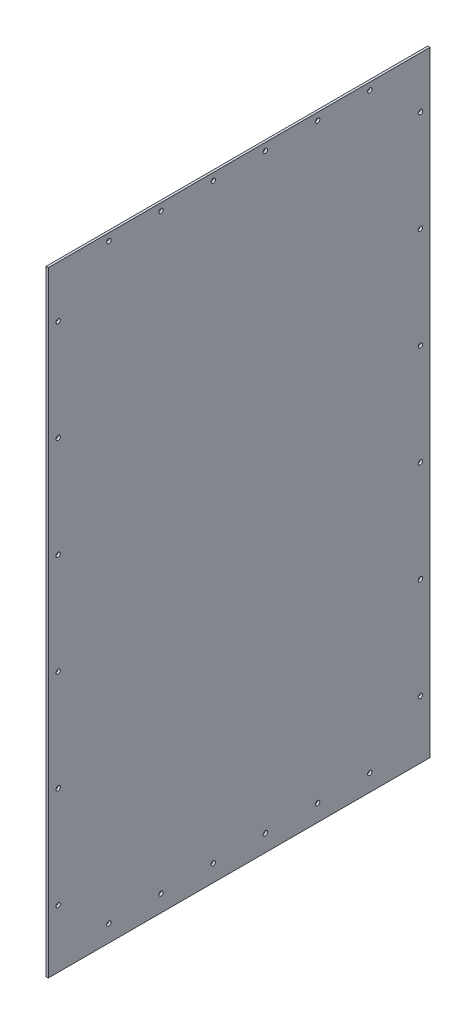
SolidWorks part; units mm, degrees
material "Acrylic (Medium-high impact)"
ref_plane "Front Plane" through (0, 0, 0) normal (0, 0, 1) x (1, 0, 0)
ref_plane "Top Plane" through (0, 0, 0) normal (0, 1, 0) x (1, 0, 0)
ref_plane "Right Plane" through (0, 0, 0) normal (1, 0, 0) x (0, 0, -1)
sketch "Sketch1" plane through (0, 0, 0) normal (1, 0, 0) x (0, 0, -1)
  line L0 (-251.1933, 404.8633) -> (-251.1933, 407.9367) construction
  line L1 (251.1933, -404.8633) -> (-251.1933, -404.8633)
  line L2 (251.1933, -404.8633) -> (251.1933, 404.8633)
  line L3 (251.1933, 404.8633) -> (-251.1933, 404.8633)
  line L4 (-251.1933, -404.8633) -> (-251.1933, 404.8633)
  line L5 (251.1933, -404.8633) -> (-251.1933, 404.8633) construction
  line L6 (251.1933, 404.8633) -> (-251.1933, -404.8633) construction
  point P0 (0, 0)
  dimension "D1" = 502.3866
  dimension "D2" = 3.0734
  dimension "D3" = 812.8
extrude "SidePanel" add sketch "Sketch1" along normal blind 3.0734
sketch "Sketch2" plane through (3.0734, 0, 0) normal (1, 0, 0) x (0, 0, -1)
  line L0 (171.9199, 404.8633) -> (171.9199, 385.8133) construction
  line L1 (251.1933, 404.8633) -> (-251.1933, 404.8633) construction
  line L3 (171.9199, -392.1633) -> (171.9199, -373.1133) construction
  line L4 (171.9199, 395.3383) -> (229.0699, 395.3383) construction
  line L5 (-251.1933, -404.8633) -> (251.1933, -404.8633) construction
  line L7 (229.0699, 395.3383) -> (248.1199, 395.3383) construction
  line L8 (248.1199, 395.3383) -> (251.1933, 395.3383) construction
  line L9 (251.1933, -404.8633) -> (251.1933, 404.8633) construction
  circle A0 centre (171.9199, 395.3383) radius 2.8956
  circle A1 centre (171.9199, -382.6383) radius 2.8956
  dimension "D3" = 5.7912
  dimension "D1" = 19.05
  dimension "D4" = 19.05
  dimension "D5" = 12.7
  dimension "D2" = 57.15
  dimension "D6" = 19.05
  dimension "D7" = 3.0734
extrude "TopBottomHoleMaster" cut sketch "Sketch2" against normal through all
pattern_linear "LPattern1" count 6 spacing 68.6906 along (0, 0, 1) of "TopBottomHoleMaster"
sketch "Sketch3" plane through (3.0734, 0, 0) normal (1, 0, 0) x (0, 0, -1)
  line L0 (251.1933, 337.4517) -> (248.1199, 337.4517) construction
  line L1 (251.1933, -404.8633) -> (251.1933, 404.8633) construction
  line L2 (248.1199, 337.4517) -> (229.0699, 337.4517) construction
  line L3 (251.1933, 404.8633) -> (251.1933, 407.9367) construction
  line L4 (251.1933, 404.8633) -> (-251.1933, 404.8633) construction
  line L5 (-250.7333, 337.4517) -> (-247.7333, 337.4517) construction
  line L6 (-250.7333, 337.4517) -> (-253.7333, 337.4517) construction
  line L8 (-247.7333, 337.4517) -> (-228.6833, 337.4517) construction
  line L11 (-253.7333, 337.4517) -> (-256.8067, 337.4517) construction
  line L12 (251.1933, -404.8633) -> (251.1933, 404.8633) construction
  circle A0 centre (-238.2083, 337.4517) radius 2.8956
  circle A1 centre (238.5949, 337.4517) radius 2.8956
  dimension "D1" = 3.0734
  dimension "D5" = 5.7912
  dimension "D2" = 19.05
  dimension "D3" = 3.0734
  dimension "D4" = 70.485
  dimension "D6" = 3
  dimension "D8" = 3.0734
  dimension "D9" = 508
extrude "RearHolesMaster" cut sketch "Sketch3" against normal through all
pattern_linear "LPattern2" count 6 spacing 133.1366 along (0, -1, 0) of "RearHolesMaster"
equation "\"Height\"= 32in"
equation "\"Width\"= 23in"
equation "\"Depth\"= 20in"
equation "\"Plexi\"= .121in"
equation "\"Cutwidth\"= .016in"
equation "\"Earsize\"= 1in + \"Cutwidth\" /2"
equation "\"Slotsize\" = 1in - \"CutWidth\" / 2"
equation "\"InnerWidth\" = \"Width\" - 2* \"Plexi\""
equation "\"InnerHeight\" = \"Height\" -2 * \"Plexi\""
equation "\"InnerDepth\" = \"Depth\" - 2*\"Plexi\""
equation "\"RearHoleSpacing\" = (\"Width\" - 2*\"RearHolesBorder\") / (\"RearNumHoles\"-1)"
equation "\"RivetDia\" = .228in"
equation "\"SlotDepth\" = \"Plexi\" + 0.75in + .005in"
equation "\"SideSlotWidth\"   = \"Plexi\"+.005in"
equation "\"SidePanelVertSpacing\" = (\"Height\"-2*(1.75-\"Plexi\")) / 5"
equation "\"BottomPanelSideHoleSpacing\" = (\"InnerDepth\"-2*(1.75-\"Plexi\")) / 4"
equation "\"D1@Sketch1\"=\"TopDepth\""
equation "\"D2@Sketch1\"=\"Plexi\""
equation "\"D1@SidePanel\"=\"Plexi\""
equation "\"MagnetThickness\"=3mm"
equation "\"MagnetDiameter\"=12mm"
equation "\"DoorPlexi\" = \"Plexi\""
equation "\"Boxsize\" = .75in"
equation "\"Boxinner\" = .625in"
equation "\"CornerCube\" = 0.75in"
equation "\"FingerLength\" = 1.125in"
equation "\"RearNumHoles\" = 7"
equation "\"RearHolesBorder\" = 2.2"
equation "\"RearBarLength\" = (\"InnerWidth\"-2*\"CornerCube\")"
equation "\"RearTopNumHoles\" = 6"
equation "\"RearTopHolesBorder\" = 2.5"
equation "\"RearTopHolesSpacing\" = (\"Width\" - 2*\"RearTopHolesBorder\") / (\"RearTopNumHoles\"-1)"
equation "\"SideTopNumHoles\" = 5"
equation "\"SideTopHoleOffset\"=\"CornerCube\"+\"FingerLength\"+\"Plexi\"+.5"
equation "\"SideTopHoleSpacing\" = (\"TopBarDepth\"-2*\"SideTopHoleOffset\") / (\"SideTopNumHoles\"-1)"
equation "\"SideHorizNumHoles\" = 6"
equation "\"SideHorizHoleBorder\" = 2.25"
equation "\"SideHorizHoleSpacing\" = (\"TopBarDepth\"-2*\"SideHorizHoleBorder\") / (\"SideHorizNumHoles\"-1)"
equation "\"SideVertNumHoles\" = 6"
equation "\"SideVertHolesBorder\" = \"CornerCube\"+\"FingerLength\"+.9"
equation "\"SideVertHoleSpacing\" = (\"InnerHeight\" - 2*\"SideVertHolesBorder\") / (\"SideVertNumHoles\"-1)"
equation "\"FrontDoorGap\" = .1in"
equation "\"TopDepth\" = \"Depth\"-\"DoorPlexi\"-\"FrontDoorGap\""
equation "\"TopBarDepth\" = \"Depth\"-\"DoorPlexi\"-\"Plexi\"-2*\"MagnetThickness\"-2*\"CornerCube\""
equation "\"D1@Sketch2\"=\"Boxsize\""
equation "\"D3@Sketch2\"=\"RivetDia\""
equation "\"D4@Sketch2\"=\"Boxsize\""
equation "\"D3@LPattern1\"=\"SideHorizHoleSpacing\""
equation "\"D1@LPattern1\"=\"SideHorizNumHoles\""
equation "\"D1@Sketch3\"=\"Plexi\""
equation "\"D2@Sketch3\"=\"Boxsize\""
equation "\"D3@Sketch3\"=\"Plexi\""
equation "\"D4@Sketch3\"=\"SideVertHolesBorder\""
equation "\"D5@Sketch3\"=\"RivetDia\""
equation "\"D3@LPattern2\"=\"SideVertHoleSpacing\""
equation "\"D1@LPattern2\"=\"SideVertNumHoles\""
equation "\"BasePlateThickness\" = 0.5in"
equation "\"SideVertBarLength\"=\"Height\"-\"BasePlateThickness\"-2*\"CornerCube\"-\"Plexi\""
equation "\"RearSideVertNumHoles\" = 7"
equation "\"RearSideVertHolesBorder\" = 2.5"
equation "\"RearSideVertHoleSpacing\" = (\"InnerHeight\" - 2*\"RearSideVertHolesBorder\") / (\"RearSideVertNumHoles\"-1)"
equation "\"D5@Sketch2\"=\"BasePlateThickness\""
equation "\"D3@Sketch1\"=\"Height\""
equation "\"D6@Sketch3\"=\"MagnetThickness\""
equation "\"D8@Sketch3\"=\"DoorPlexi\""
equation "\"D9@Sketch3\"=\"Depth\""
equation "\"D7@Sketch2\"=\"Plexi\""
equation "\"D6@Sketch2\"=\"Boxsize\""
equation "\"D2@Sketch2\"=\"SideHorizHoleBorder\""
